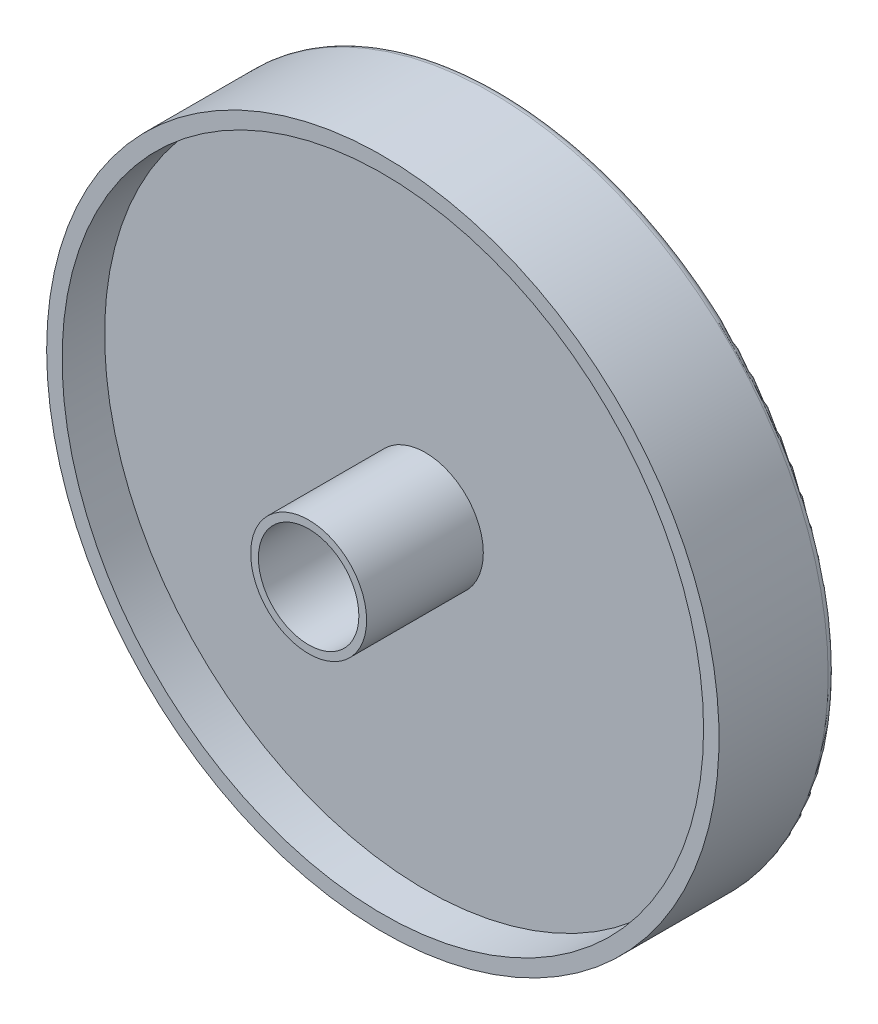
SolidWorks part; units mm, degrees
material "3.1355 (EN-AW 2024)"
ref_plane "Front" through (0, 0, 0) normal (0, 0, 1) x (1, 0, 0)
ref_plane "Top" through (0, 0, 0) normal (0, 1, 0) x (1, 0, 0)
ref_plane "Right" through (0, 0, 0) normal (1, 0, 0) x (0, 0, -1)
sketch "Эскиз1" plane through (0, 0, 0) normal (0, 1, 0) x (1, 0, 0)
  line L0 (0, 0) -> (-43.5, 0)
  line L1 (-43.5, 0) -> (-43.5, 15)
  line L2 (-43.5, 15) -> (-20, 18)
  line L3 (-20, 18) -> (0, 18)
  line L4 (0, 18) -> (0, 0)
  dimension "D1" = 15
  dimension "D2" = 43.5
  dimension "D3" = 20
  dimension "D4" = 18
revolve "Повернуть1" add sketch "Эскиз1" angle 360 about L4
sketch "Эскиз2" plane through (0, 0, 0) normal (0, 0, 1) x (1, 0, 0)
  circle A0 centre (0, 0) radius 41.5
  dimension "D1" = 83
extrude "Вырез-Вытянуть1" cut sketch "Эскиз2" against normal blind 13
sketch "Эскиз3" plane through (0, 0, -18) normal (0, 0, -1) x (-1, 0, 0)
  circle A0 centre (0, 0) radius 6.5
  dimension "D1" = 13
extrude "Вырез-Вытянуть2" cut sketch "Эскиз3" against normal through all
sketch "Эскиз4" plane through (0, 0, -13) normal (0, 0, 1) x (1, 0, 0)
  circle A0 centre (0, 0) radius 7.5
  circle A1 centre (0, 0) radius 6.5 construction
  circle A2 centre (0, 0) radius 6.5
  dimension "D1" = 15
extrude "Бобышка-Вытянуть1" add sketch "Эскиз4" along normal blind 22.6
sketch "Эскиз5" plane through (0, 0, -18) normal (0, 0, -1) x (-1, 0, 0)
  line L0 (0, 0) -> (-12.3744, 12.3744) construction
  line L1 (0, 0) -> (-17.5, 0) construction
  line L2 (0, 0) -> (12.3744, 12.3744) construction
  line L3 (0, 0) -> (12.3744, -12.3744) construction
  line L4 (0, 0) -> (-12.3744, -12.3744) construction
  circle A0 centre (0, 0) radius 12.5 construction
  circle A1 centre (0, 0) radius 17.5 construction
  point P4 (-12.5, 0)
  point P5 (0, 12.5)
  point P6 (12.5, 0)
  point P7 (0, -12.5)
  point P8 (-17.5, 0)
  point P9 (0, 17.5)
  point P10 (17.5, 0)
  point P11 (0, -17.5)
  point P20 (0, 0)
  dimension "D1" = 25
  dimension "D2" = 35
  dimension "D3" = 45
  dimension "D4" = 4
hole_wizard "Отверстие обработанное метчиком M3x0.51" positions "Эскиз7" profile "Эскиз6" tap size "M3x0.5" standard "Ansi Metric" end condition through all
sketch "Эскиз7" plane through (0, 0, -18) normal (0, 0, -1) x (-1, 0, 0)
  point P0 (-12.3744, 12.3744)
  point P3 (0, 17.5)
  point P6 (12.3744, 12.3744)
  point P9 (17.5, 0)
  point P12 (12.3744, -12.3744)
  point P15 (0, -17.5)
  point P18 (-12.3744, -12.3744)
  point P21 (-17.5, 0)
  point P24 (-12.5, 0)
  point P27 (0, 12.5)
  point P30 (12.5, 0)
  point P33 (0, -12.5)
sketch "Эскиз6" plane through (12.3744, 12.3744, -18) normal (1, 0, 0) x (0, 1, 0)
  line L0 (0, 0) -> (0, 27.6)
  line L1 (0, 27.6) -> (1.25, 27.6)
  line L2 (1.25, 27.6) -> (1.25, 0)
  line L5 (1.25, 0) -> (0, 0)
  line L11 (0, -6.35) -> (0, 107.95) construction
  dimension "Диаметр проходного сверла" = 2.5
  dimension "Глубина проходного сверла" = 27.6
cosmetic thread "Отверстие резьбы1" parameters "D2"=3
cosmetic thread "Отверстие резьбы2" parameters "D2"=3
cosmetic thread "Отверстие резьбы3" parameters "D2"=3
cosmetic thread "Отверстие резьбы4" parameters "D2"=3
cosmetic thread "Отверстие резьбы5" parameters "D2"=3
cosmetic thread "Отверстие резьбы6" parameters "D2"=3
cosmetic thread "Отверстие резьбы7" parameters "D2"=3
cosmetic thread "Отверстие резьбы8" parameters "D2"=3
cosmetic thread "Отверстие резьбы9" parameters "D2"=3
cosmetic thread "Отверстие резьбы10" parameters "D2"=3
cosmetic thread "Отверстие резьбы11" parameters "D2"=3
cosmetic thread "Отверстие резьбы12" parameters "D2"=3
fillet "Скругление1" radius 1 2 edges at (-20, 0, -18) (-43.5, 0, -15)
sketch "Эскиз8" plane through (0, 0, -13) normal (0, 0, 1) x (1, 0, 0)
  circle A0 centre (0, 0) radius 7.5 construction
  circle A1 centre (0, 0) radius 41.5
  circle A2 centre (0, 0) radius 41.5
  circle A3 centre (0, 0) radius 7.5
  dimension "D1" = 0
extrude "Бобышка-Вытянуть2" add sketch "Эскиз8" along normal blind 7.5
